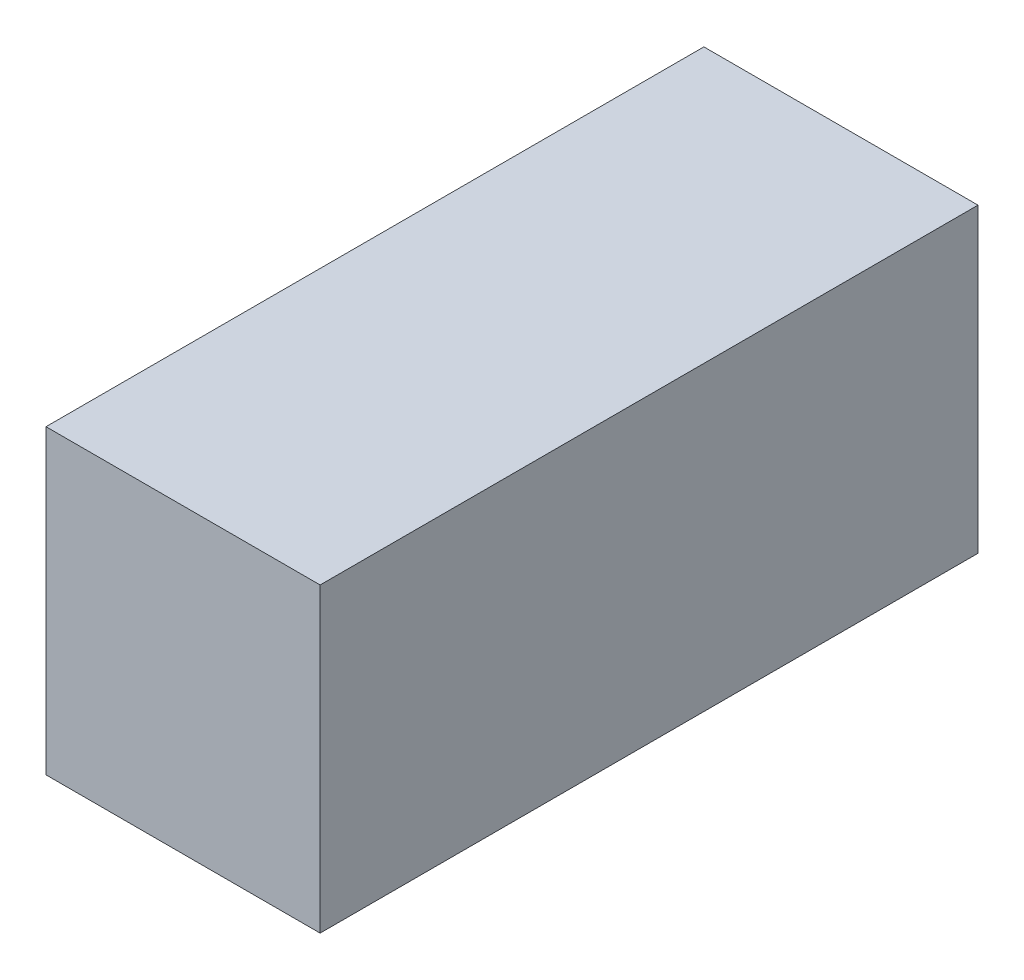
SolidWorks part; units mm, degrees
ref_plane "Front Plane" through (0, 0, 0) normal (0, 0, 1) x (1, 0, 0)
ref_plane "Top Plane" through (0, 0, 0) normal (0, 1, 0) x (1, 0, 0)
ref_plane "Right Plane" through (0, 0, 0) normal (1, 0, 0) x (0, 0, -1)
sketch "Sketch1" plane through (0, 0, 0) normal (0, 1, 0) x (1, 0, 0)
  line L1 (-15.875, 38.1) -> (15.875, 38.1)
  line L2 (-15.875, 38.1) -> (-15.875, -38.1)
  line L3 (-15.875, -38.1) -> (15.875, -38.1)
  line L4 (15.875, 38.1) -> (15.875, -38.1)
  point P4 (0, 38.1)
  point P6 (-15.875, 0)
  dimension "D1" = 31.75
  dimension "D2" = 76.2
extrude "Boss-Extrude1" add sketch "Sketch1" along normal blind 34.925
